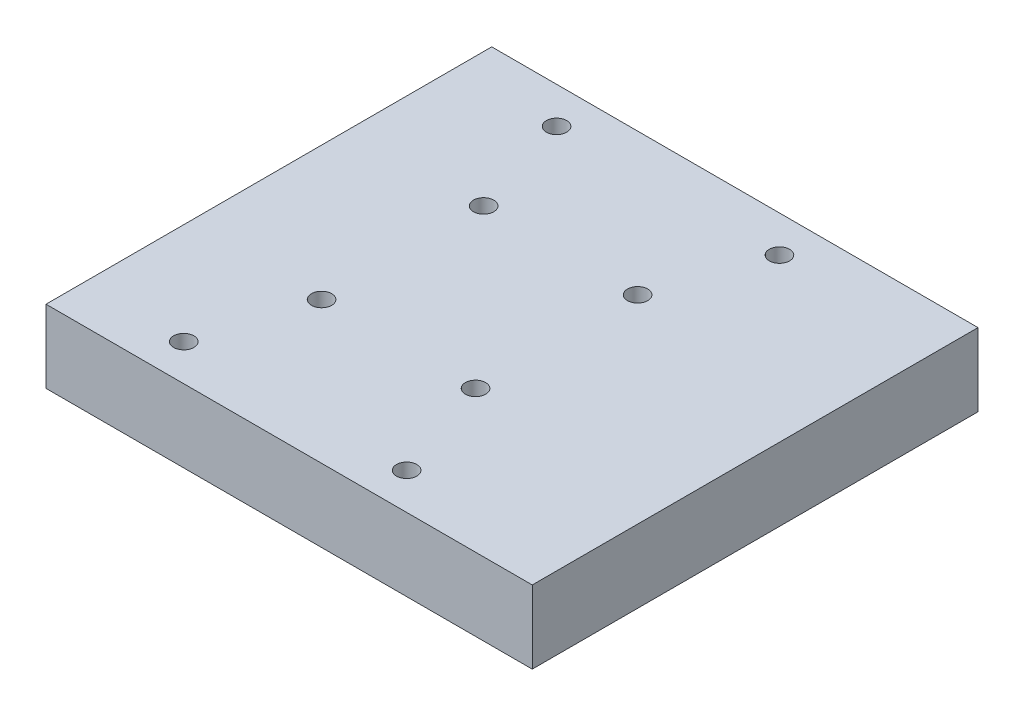
SolidWorks part; units mm, degrees
ref_plane "Front Plane" through (0, 0, 0) normal (0, 0, 1) x (1, 0, 0)
ref_plane "Top Plane" through (0, 0, 0) normal (0, 1, 0) x (1, 0, 0)
ref_plane "Right Plane" through (0, 0, 0) normal (1, 0, 0) x (0, 0, -1)
sketch "Sketch1" plane through (0, 0, 0) normal (0, 1, 0) x (1, 0, 0)
  line L1 (-60, 55) -> (60, 55)
  line L2 (-60, 55) -> (-60, -55)
  line L3 (-60, -55) -> (60, -55)
  line L4 (60, 55) -> (60, -55)
  line L5 (-60, 55) -> (60, -55) construction
  line L6 (-60, -55) -> (60, 55) construction
  point P0 (0, 0)
  dimension "D1" = 110
  dimension "D2" = 120
extrude "Boss-Extrude1" add sketch "Sketch1" along normal blind 18
hole_wizard "Ø5.0 (5) Diameter Hole1" positions "Sketch3" profile "Sketch2" hole size "Ø5.0" standard "ISO" end condition through all
sketch "Sketch3" plane through (0, 0, 0) normal (0, -1, 0) x (-1, 0, 0)
  line L0 (-60, 55) -> (60, 55) construction
  line L1 (60, -55) -> (-60, -55) construction
  line L2 (60, 55) -> (60, -55) construction
  point P0 (-20, 46)
  point P2 (35, 46)
  point P4 (35, -46)
  point P6 (-20, -46)
  dimension "D1" = 9
  dimension "D2" = 9
  dimension "D3" = 9
  dimension "D4" = 9
  dimension "D5" = 55
  dimension "D6" = 25
  dimension "D7" = 55
  dimension "D8" = 25
sketch "Sketch2" plane through (20, 0, -46) normal (1, 0, 0) x (0, 0, -1)
  line L0 (0, 0) -> (0, 18)
  line L1 (0, 18) -> (2.5, 18)
  line L2 (2.5, 18) -> (2.5, 0)
  line L5 (2.5, 0) -> (0, 0)
  line L11 (0, -6.35) -> (0, 107.95) construction
  dimension "Thru Hole Dia." = 5
  dimension "Thru Hole Depth" = 18
hole_wizard "Ø5.0 (5) Diameter Hole3" positions "Sketch7" profile "Sketch6" hole size "Ø5.0" standard "ISO" end condition through all
sketch "Sketch7" plane through (0, 0, 0) normal (0, -1, 0) x (-1, 0, 0)
  line L0 (60, -55) -> (-60, -55) construction
  line L1 (-60, 55) -> (60, 55) construction
  line L2 (-60, -55) -> (-60, 55) construction
  point P0 (27, 20)
  point P2 (-11, 20)
  point P4 (-11, -20)
  point P6 (27, -20)
  dimension "D1" = 35
  dimension "D2" = 35
  dimension "D3" = 35
  dimension "D4" = 35
  dimension "D5" = 49
  dimension "D6" = 49
  dimension "D7" = 38
  dimension "D8" = 38
sketch "Sketch6" plane through (-27, 0, -20) normal (1, 0, 0) x (0, 0, -1)
  line L0 (0, 0) -> (0, 18)
  line L1 (0, 18) -> (2.5, 18)
  line L2 (2.5, 18) -> (2.5, 0)
  line L5 (2.5, 0) -> (0, 0)
  line L11 (0, -6.35) -> (0, 107.95) construction
  dimension "Thru Hole Dia." = 5
  dimension "Thru Hole Depth" = 18
